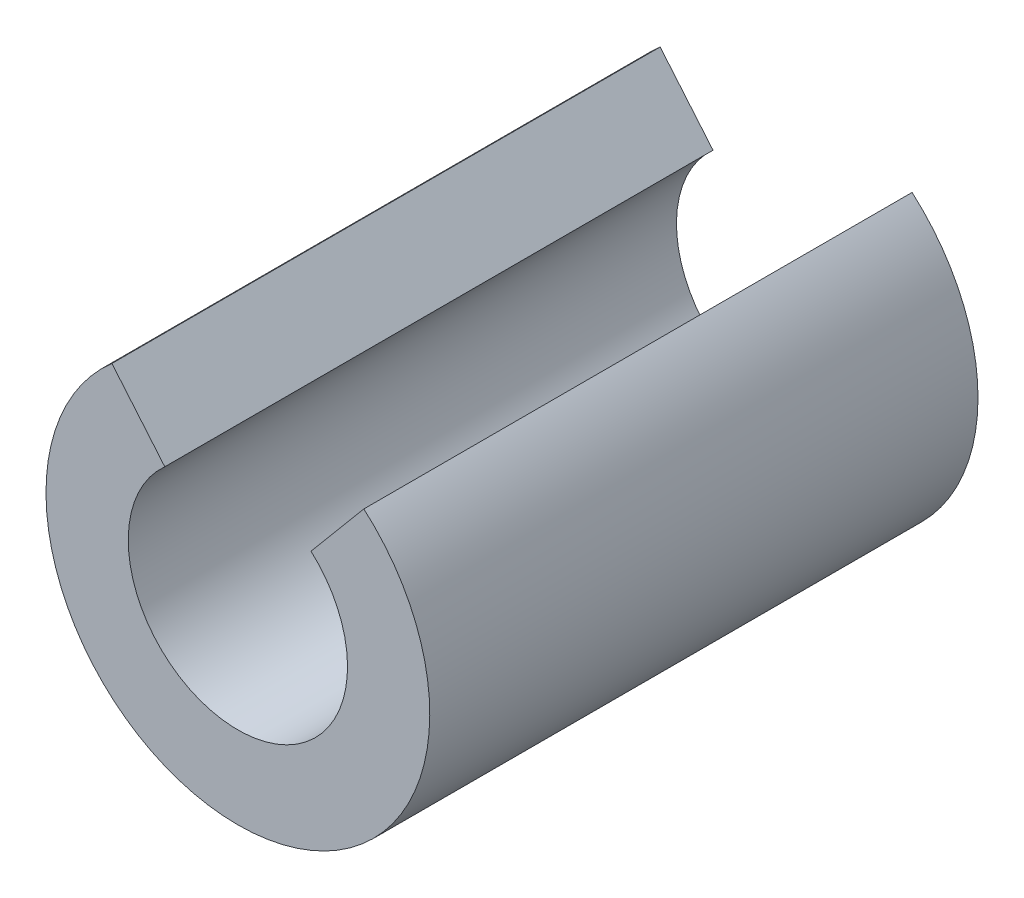
SolidWorks part; units mm, degrees
ref_plane "前视基准面" through (0, 0, 0) normal (0, 0, 1) x (1, 0, 0)
ref_plane "上视基准面" through (0, 0, 0) normal (0, 1, 0) x (1, 0, 0)
ref_plane "右视基准面" through (0, 0, 0) normal (1, 0, 0) x (0, 0, -1)
sketch "草图1" plane through (0, 0, 0) normal (0, 0, 1) x (1, 0, 0)
  line L0 (-6.8934, 7.9203) -> (-4, 4.4721)
  line L1 (6.8934, 7.9203) -> (4, 4.4721)
  arc A0 (-4, 4.4721) -> (4, 4.4721) centre (0, 0) ccw
  arc A1 (-6.8934, 7.9203) -> (6.8934, 7.9203) centre (0, 0) ccw
  point P8 (0, 0)
  point P9 (0, 0)
  dimension "D1" = 12
  dimension "D2" = 21
  dimension "D3" = 80
  dimension "D4" = 8
extrude "凸台-拉伸1" add sketch "草图1" along normal mid plane 30
